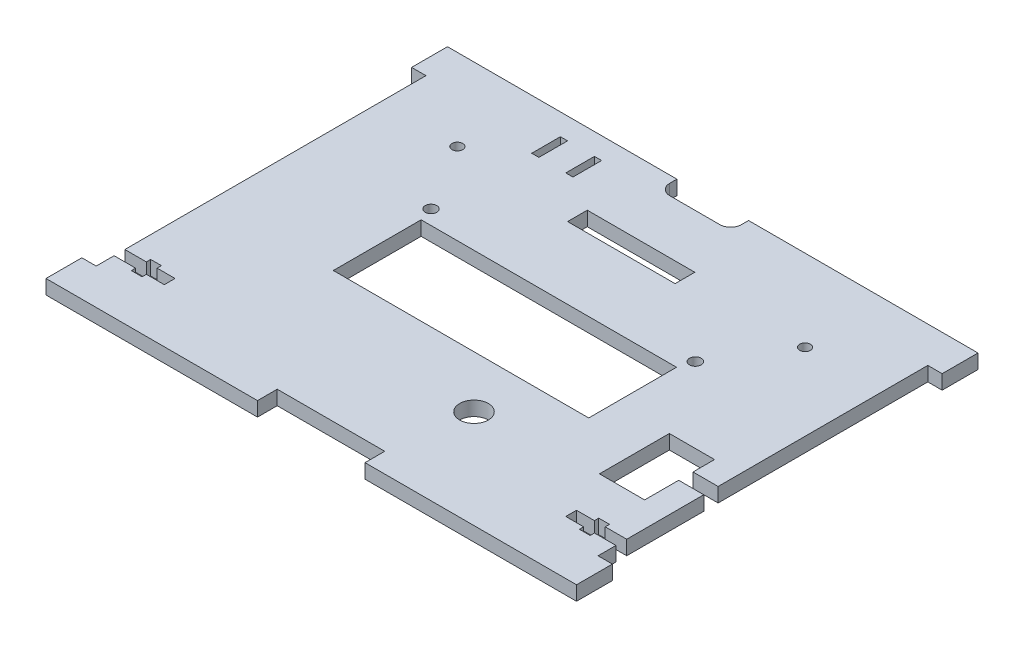
SolidWorks part; units mm, degrees
ref_plane "Front Plane" through (0, 0, 0) normal (0, 0, 1) x (1, 0, 0)
ref_plane "Top Plane" through (0, 0, 0) normal (0, 1, 0) x (1, 0, 0)
ref_plane "Right Plane" through (0, 0, 0) normal (1, 0, 0) x (0, 0, -1)
sketch "Sketch1" plane through (0, 0, 0) normal (0, 1, 0) x (1, 0, 0)
  line L0 (85, 0) -> (140, 0)
  line L1 (0, 0) -> (55, 0)
  line L2 (0, 10) -> (0, 15)
  line L3 (0, 112) -> (60, 112)
  line L4 (140, 10) -> (140, 15)
  line L5 (0, 112) -> (-4, 112)
  line L6 (80, 112) -> (140, 112)
  line L7 (0, 102) -> (-4, 102)
  line L8 (-4, 112) -> (-4, 102)
  line L9 (0, 0) -> (-4, 0)
  line L10 (55, 0) -> (55, 5.5)
  line L11 (0, 10) -> (-4, 10)
  line L12 (-4, 0) -> (-4, 10)
  line L13 (140, 112) -> (144, 112)
  line L14 (55, 5.5) -> (85, 5.5)
  line L15 (140, 102) -> (144, 102)
  line L16 (144, 112) -> (144, 102)
  line L17 (140, 0) -> (144, 0)
  line L18 (85, 0) -> (85, 5.5)
  line L19 (140, 10) -> (144, 10)
  line L20 (144, 0) -> (144, 10)
  line L21 (55, 92) -> (85, 92)
  line L22 (55, 92) -> (55, 86.5)
  line L23 (55, 86.5) -> (85, 86.5)
  line L24 (85, 92) -> (85, 86.5)
  line L25 (120.4, 49.5) -> (133, 49.5)
  line L26 (120.4, 49.5) -> (120.4, 30)
  line L27 (120.4, 30) -> (133, 30)
  line L28 (133, 49.5) -> (133, 43.5)
  line L29 (33.5, 106) -> (35.5, 106)
  line L30 (33.5, 106) -> (33.5, 98)
  line L31 (33.5, 98) -> (35.5, 98)
  line L32 (35.5, 106) -> (35.5, 98)
  line L33 (43, 106) -> (45, 106)
  line L34 (43, 106) -> (43, 98)
  line L35 (43, 98) -> (45, 98)
  line L36 (45, 106) -> (45, 98)
  line L37 (34.15, 66.5) -> (105.4, 66.5)
  line L38 (34.15, 66.5) -> (34.15, 42)
  line L39 (34.15, 42) -> (105.4, 42)
  line L40 (105.4, 66.5) -> (105.4, 42)
  line L41 (140, 43.5) -> (140, 102)
  line L42 (60, 112) -> (60, 107)
  line L43 (60, 107) -> (80, 107)
  line L44 (80, 112) -> (80, 107)
  line L45 (133, 43.5) -> (140, 43.5)
  line L46 (140, 18) -> (140, 39.5)
  line L47 (133, 39.5) -> (140, 39.5)
  line L48 (134, 15) -> (134, 13.8)
  line L49 (133, 39.5) -> (133, 30)
  line L50 (140, 18) -> (134, 18)
  line L51 (0, 18) -> (0, 102)
  line L52 (140, 15) -> (134, 15)
  line L53 (126, 18) -> (126, 15)
  line L54 (131, 19.2) -> (134, 19.2)
  line L55 (131, 19.2) -> (131, 18)
  line L56 (131, 13.8) -> (134, 13.8)
  line L57 (134, 19.2) -> (134, 18)
  line L58 (131, 15) -> (131, 13.8)
  line L59 (131, 18) -> (126, 18)
  line L60 (131, 15) -> (126, 15)
  line L61 (6, 15) -> (6, 13.8)
  line L62 (0, 15) -> (6, 15)
  line L64 (0, 18) -> (6, 18)
  line L65 (14, 15) -> (14, 18)
  line L66 (6, 19.2) -> (9, 19.2)
  line L67 (6, 19.2) -> (6, 18)
  line L68 (6, 13.8) -> (9, 13.8)
  line L69 (9, 19.2) -> (9, 18)
  line L70 (9, 15) -> (9, 13.8)
  line L71 (9, 18) -> (14, 18)
  line L72 (9, 15) -> (14, 15)
  circle A0 centre (21.5, 89.25) radius 1.5
  circle A1 centre (118.5, 89.25) radius 1.5
  circle A2 centre (87.9, 27.5) radius 4
  circle A3 centre (32.9, 70.5) radius 1.625
  circle A4 centre (106.65, 70.5) radius 1.625
  dimension "D20" = 3
  dimension "D21" = 3
  dimension "D40" = 8
  dimension "D47" = 3.25
  dimension "D48" = 3.25
  dimension "D1" = 140
  dimension "D2" = 112
  dimension "D3" = 4
  dimension "D4" = 10
  dimension "D5" = 10
  dimension "D6" = 4
  dimension "D7" = 4
  dimension "D8" = 10
  dimension "D9" = 10
  dimension "D10" = 4
  dimension "D11" = 30
  dimension "D12" = 55
  dimension "D13" = 5.5
  dimension "D14" = 81
  dimension "D15" = 30
  dimension "D16" = 5.5
  dimension "D17" = 55
  dimension "D18" = 33.5
  dimension "D19" = 33.5
  dimension "D22" = 2.75
  dimension "D23" = 2.75
  dimension "D24" = 19.5
  dimension "D25" = 12.6
  dimension "D26" = 7
  dimension "D27" = 30
  dimension "D28" = 2
  dimension "D29" = 6
  dimension "D30" = 8
  dimension "D31" = 33.5
  dimension "D32" = 2
  dimension "D33" = 6
  dimension "D34" = 8
  dimension "D35" = 7.5
  dimension "D36" = 71.25
  dimension "D37" = 24.5
  dimension "D38" = 20
  dimension "D39" = 15
  dimension "D41" = 14.5
  dimension "D42" = 17.5
  dimension "D43" = 4
  dimension "D44" = 4
  dimension "D45" = 1.25
  dimension "D46" = 1.25
  dimension "D49" = 20
  dimension "D50" = 5
  dimension "D51" = 5
  dimension "D52" = 4
  dimension "D53" = 6
  dimension "D54" = 5
  dimension "D55" = 3
  dimension "D56" = 6
  dimension "D57" = 3
  dimension "D58" = 1.2
  dimension "D59" = 5.4
  dimension "D60" = 14
  dimension "D61" = 5
  dimension "D62" = 3
  dimension "D63" = 14
  dimension "D64" = 6
  dimension "D65" = 3
  dimension "D66" = 1.2
  dimension "D67" = 5.4
extrude "Boss-Extrude1" add sketch "Sketch1" along normal blind 4
fillet "Fillet1" radius 3 1 edges at (60, 2, -107)
fillet "Fillet2" radius 3 1 edges at (80, 2, -107)
